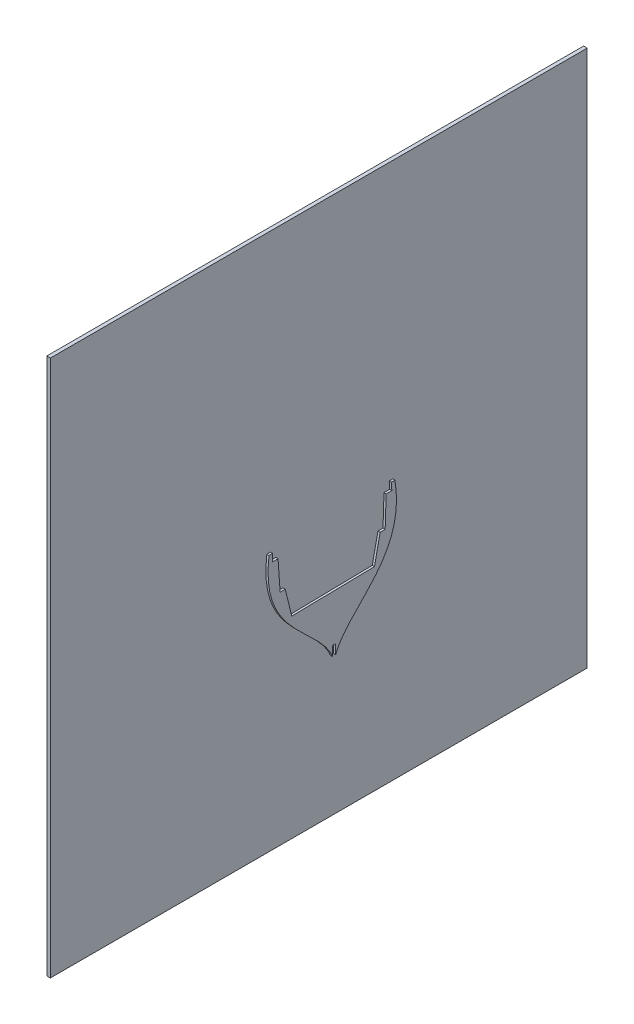
SolidWorks part; units mm, degrees
ref_plane "Plan de face" through (0, 0, 0) normal (0, 0, 1) x (1, 0, 0)
ref_plane "Plan de dessus" through (0, 0, 0) normal (0, 1, 0) x (1, 0, 0)
ref_plane "Plan de droite" through (0, 0, 0) normal (1, 0, 0) x (0, 0, -1)
sketch "Esquisse1" plane through (0, 0, 0) normal (0, 0, 1) x (1, 0, 0)
  point P0 (-20, 0)
  dimension "D1" = 20
sketch3d "Esquisse3D1"
  line L1 (-20, 1121.2893, 777.275) -> (-20, 1121.2893, -722.725)
  line L2 (-20, 1121.2893, 777.275) -> (-20, -378.7107, 777.275)
  line L3 (-20, -378.7107, 777.275) -> (-20, -378.7107, -722.725)
  line L4 (-20, 1121.2893, -722.725) -> (-20, -378.7107, -722.725)
  dimension "D1" = 1500
  dimension "D2" = 1500
extrude "Boss.-Extru.2" add sketch "Esquisse3D1" along direction (1, 0, 0) on the side of the normal blind 10 contours L2 L1 L4 L3
sketch "Esquisse4" plane through (-10, 0, 0) normal (1, 0, 0) x (0, 0, -1)
  line L0 (0, 0) -> (-7.701, 425.1082) construction
  line L1 (169.3944, 339.9131) -> (-188.5193, 333.4294) construction
  line L2 (-187.2006, 249.23) -> (169.0622, 255.6839) construction
  line L3 (-144.268, 175.2448) -> (126.4811, 180.1495) construction
sketch "Esquisse5" plane through (0, 0, 0) normal (1, 0, 0) x (0, 0, -1)
  line L0 (-7.701, 425.1082) -> (0, 0) construction
  line L2 (0, 0) -> (-0.2841, 15.6805) construction
  line L3 (-0.2841, 15.6805) -> (12.0527, 120.1045) construction
  line L4 (12.0527, 120.1045) -> (206.6118, 134.647) construction
  line L5 (206.6118, 134.647) -> (169.4989, 360.5185) construction
  line L8 (169.4989, 360.5185) -> (159.4989, 360.3373)
  line L9 (159.4989, 360.3373) -> (160.7679, 339.7568)
  line L10 (169.3944, 339.9131) -> (-188.5193, 333.4294) construction
  line L11 (160.7679, 339.7568) -> (144.9235, 339.4698)
  line L12 (144.9235, 339.4698) -> (142.1525, 255.1964)
  line L13 (-187.2006, 249.23) -> (169.0622, 255.6839) construction
  line L14 (142.1525, 255.1964) -> (127.9947, 254.9399)
  line L15 (127.9947, 254.9399) -> (112.2991, 179.8926)
  line L16 (-144.268, 175.2448) -> (126.4811, 180.1495) construction
  line L17 (112.2991, 179.8926) -> (-118.7409, 175.7072)
  line L18 (0, 0) -> (-0.2841, 15.6805) construction
  line L19 (-0.2841, 15.6805) -> (-16.3948, 119.5891) construction
  line L20 (-16.3948, 119.5891) -> (-211.353, 127.0754) construction
  line L21 (-211.353, 127.0754) -> (-182.4452, 354.1429) construction
  line L22 (-137.1444, 250.1368) -> (-118.7409, 175.7072)
  line L23 (-151.3022, 249.8804) -> (-137.1444, 250.1368)
  line L24 (-157.1236, 333.9981) -> (-151.3022, 249.8804)
  line L25 (-172.968, 333.7111) -> (-157.1236, 333.9981)
  line L26 (-172.4452, 354.3241) -> (-172.968, 333.7111)
  line L27 (-182.4452, 354.1429) -> (-172.4452, 354.3241)
  spline S0 degree 4 poles (0, 0) (-0.2841, 15.6805) (12.0527, 120.1045) (206.6118, 134.647) (169.4989, 360.5185) knots 0 0 0 0 0 1 1 1 1 1
  spline S1 degree 4 poles (0, 0) (-0.2841, 15.6805) (-16.3948, 119.5891) (-211.353, 127.0754) (-182.4452, 354.1429) knots 0 0 0 0 0 1 1 1 1 1
  point P30 (-3.2209, 177.7999)
  dimension "D1" = 10
extrude "Boss.-Extru.3" add sketch "Esquisse5" along normal blind 6 separate body
sketch "Esquisse6" plane through (6, 0, 0) normal (1, 0, 0) x (0, 0, -1)
  line L0 (-4.8783, 20.8021) -> (-5.3674, 47.8021)
  line L1 (-5.3674, 47.8021) -> (3.6326, 47.9652)
  line L2 (3.6326, 47.9652) -> (4.1217, 20.9652)
  line L3 (4.1217, 20.9652) -> (117.0633, -47.527)
  line L4 (117.0633, -47.527) -> (-85.2277, -65.22)
  line L5 (-85.2277, -65.22) -> (-4.8783, 20.8021)
  line L6 (-4.8783, 20.8021) -> (4.1217, 20.9652) construction
  line L7 (-144.268, 175.2448) -> (126.4811, 180.1495) construction
  spline S0 degree 4 poles (-182.4452, 354.1429) (-211.353, 127.0754) (-16.3948, 119.5891) (-0.2841, 15.6805) (0, 0) knots 0 0 0 0 0 1 1 1 1 1 construction
  spline S1 degree 4 poles (0, 0) (-0.2841, 15.6805) (12.0527, 120.1045) (206.6118, 134.647) (169.4989, 360.5185) knots 0 0 0 0 0 1 1 1 1 1 construction
  dimension "D1" = 9
  dimension "D2" = 27
extrude "Enlèv. mat.-Extru.1" cut sketch "Esquisse6" against normal blind 6
